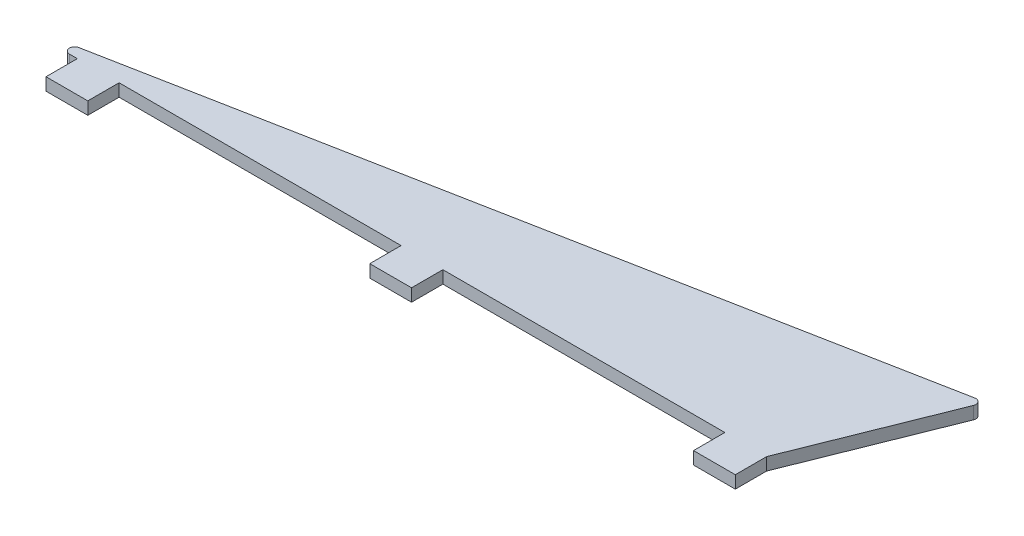
SolidWorks part; units mm, degrees
ref_plane "Front Plane" through (0, 0, 0) normal (0, 0, 1) x (1, 0, 0)
ref_plane "Top Plane" through (0, 0, 0) normal (0, 1, 0) x (1, 0, 0)
ref_plane "Right Plane" through (0, 0, 0) normal (1, 0, 0) x (0, 0, -1)
sketch "Esboço1" plane through (0, 0, 0) normal (0, 1, 0) x (1, 0, 0)
  line L1 (-4.2339, 19.955) -> (355.5077, 89.1361)
  line L2 (0, 0) -> (20, 0)
  line L3 (20, 0) -> (20, 15)
  line L4 (20, 15) -> (155, 15)
  line L5 (155, 15) -> (155, 0)
  line L6 (155, 0) -> (175, 0)
  line L7 (175, 0) -> (175, 15)
  line L8 (175, 15) -> (310, 15)
  line L9 (310, 15) -> (310, 0)
  line L10 (310, 0) -> (330, 0)
  line L11 (330, 0) -> (330, 15)
  line L12 (330, 15) -> (358.301, 85.7526)
  line L13 (20, 15) -> (-30, 15) construction
  line L15 (-3.7618, 15) -> (0, 15)
  line L16 (0, 0) -> (0, 15)
  arc A0 (-3.7618, 15) -> (-4.2339, 19.955) centre (-3.7618, 17.5) cw
  arc A1 (355.5077, 89.1361) -> (358.301, 85.7526) centre (355.9799, 86.6811) cw
  point P8 (-58.995, 15)
  point P16 (0, 0)
  point P17 (10, 0)
  point P18 (165, 0)
  point P19 (320, 0)
  point P20 (0, 0)
  point P22 (0, 0)
  point P23 (0, 0)
  point P24 (0, 0)
  point P25 (0, 0)
  point P26 (-54.6725, 15)
  point P31 (360, 90)
  dimension "D12" = 2.5
  dimension "D13" = 2.5
  dimension "D1" = 15
  dimension "D2" = 155
  dimension "D3" = 20
  dimension "D4" = 20
  dimension "D5" = 20
  dimension "D6" = 155
  dimension "D7" = 75
  dimension "D8" = 15
  dimension "D9" = 30
  dimension "D10" = 15
  dimension "D11" = 30
extrude "Ressalto-extrusão1" add sketch "Esboço1" along normal blind 6
